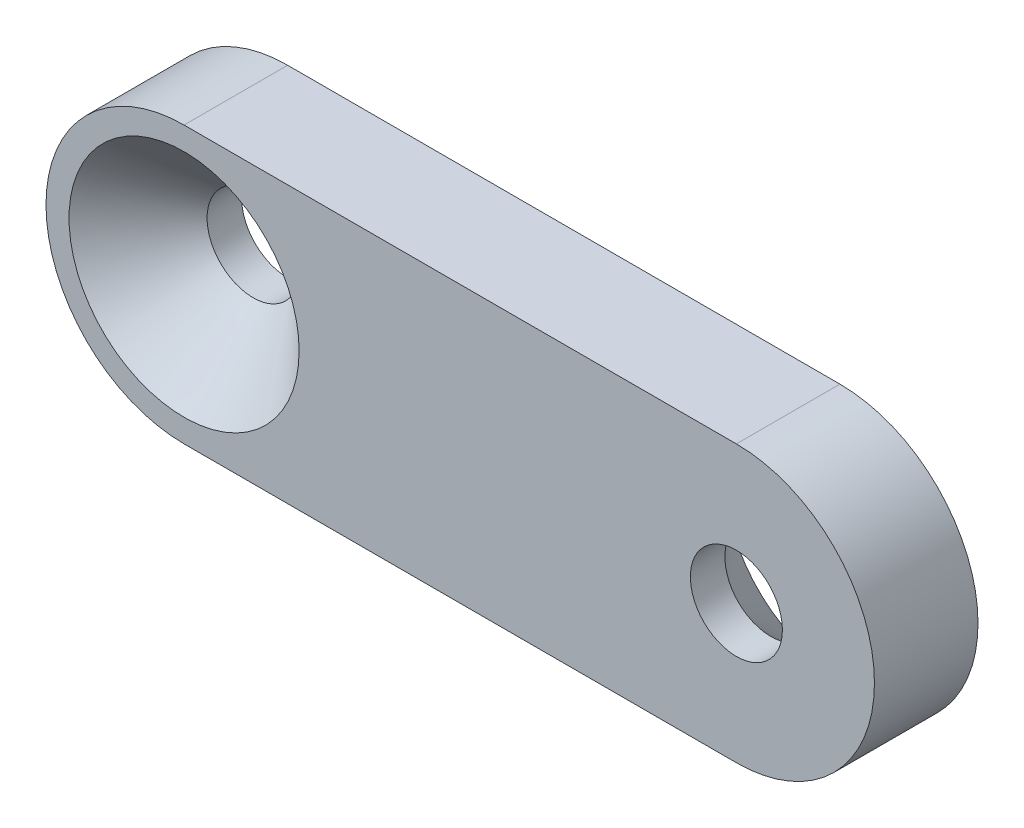
SolidWorks part; units mm, degrees
material "3D printed plastic"
ref_plane "Front Plane" through (0, 0, 0) normal (0, 0, 1) x (1, 0, 0)
ref_plane "Top Plane" through (0, 0, 0) normal (0, 1, 0) x (1, 0, 0)
ref_plane "Right Plane" through (0, 0, 0) normal (1, 0, 0) x (0, 0, -1)
sketch "Sketch1" plane through (0, 0, 0) normal (0, 0, 1) x (1, 0, 0)
  line L0 (-12, 0) -> (12, 0) construction
  line L1 (-12, 6) -> (12, 6)
  line L2 (-12, -6) -> (12, -6)
  arc A0 (-12, 6) -> (-12, -6) centre (-12, 0) ccw
  arc A1 (12, -6) -> (12, 6) centre (12, 0) ccw
  circle A2 centre (-12, 0) radius 2
  circle A3 centre (12, 0) radius 2
  point P3 (0, 0)
  dimension "D3" = 4
  dimension "D1" = 12
  dimension "D2" = 24
extrude "Boss-Extrude1" add sketch "Sketch1" along normal blind 4.5
chamfer "Chamfer1" distance 3 angle 45 1 edges at (14, 0, 0)
chamfer "Chamfer2" distance 3 angle 45 1 edges at (-10, 0, 4.5)
